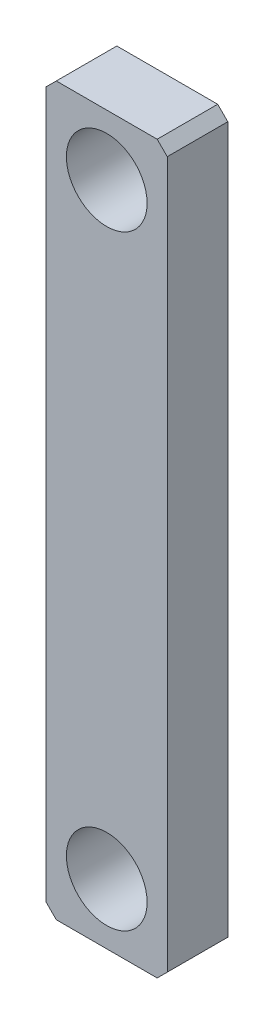
SolidWorks part; units mm, degrees
material "2024-T3"
ref_plane "正面" through (0, 0, 0) normal (0, 0, 1) x (1, 0, 0)
ref_plane "平面" through (0, 0, 0) normal (0, 1, 0) x (1, 0, 0)
ref_plane "右側面" through (0, 0, 0) normal (1, 0, 0) x (0, 0, -1)
sketch "ｽｹｯﾁ1" plane through (0, 0, 0) normal (0, 0, 1) x (1, 0, 0)
  line L1 (0, 0) -> (12, 0)
  line L2 (0, 0) -> (0, 72)
  line L3 (0, 72) -> (12, 72)
  line L4 (12, 0) -> (12, 72)
  dimension "D1" = 72
  dimension "D2" = 12
extrude "ﾎﾞｽ - 押し出し1" add sketch "ｽｹｯﾁ1" along normal blind 6
sketch "ｽｹｯﾁ2" plane through (0, 0, 6) normal (0, 0, 1) x (1, 0, 0)
  circle A0 centre (6, 66) radius 4
  dimension "D1" = 8
  dimension "D2" = 6
  dimension "D3" = 6
extrude "ｶｯﾄ - 押し出し1" cut sketch "ｽｹｯﾁ2" against normal through all
sketch "ｽｹｯﾁ3" plane through (0, 0, 6) normal (0, 0, 1) x (1, 0, 0)
  circle A0 centre (6, 6) radius 4
  dimension "D1" = 8
  dimension "D2" = 6
  dimension "D3" = 6
extrude "ｶｯﾄ - 押し出し2" cut sketch "ｽｹｯﾁ3" against normal through all
chamfer "面取り1" distance 1 angle 45 4 edges at (0, 0, 3) (12, 0, 3) (12, 72, 3) (0, 72, 3)
